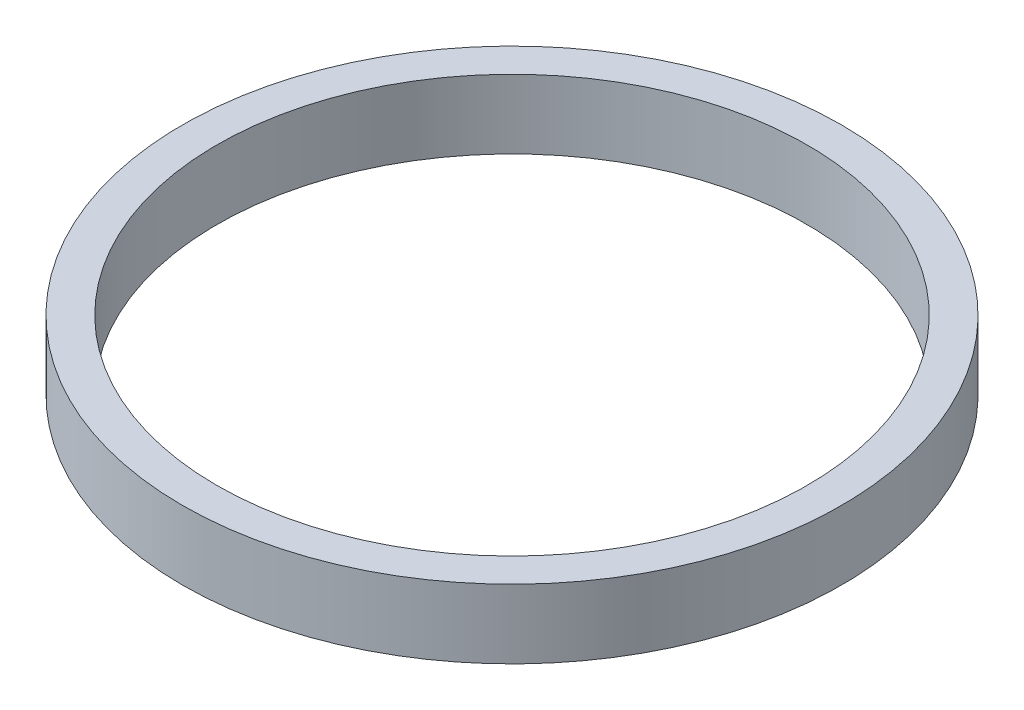
SolidWorks part; units mm, degrees
ref_plane "Front Plane" through (0, 0, 0) normal (0, 0, 1) x (1, 0, 0)
ref_plane "Top Plane" through (0, 0, 0) normal (0, 1, 0) x (1, 0, 0)
ref_plane "Right Plane" through (0, 0, 0) normal (1, 0, 0) x (0, 0, -1)
sketch "Sketch1" plane through (0, 0, 0) normal (0, 1, 0) x (1, 0, 0)
  circle A0 centre (0, 0) radius 42.75
  circle A1 centre (0, 0) radius 47.75
  dimension "D1" = 85.5
  dimension "D2" = 95.5
extrude "Boss-Extrude1" add sketch "Sketch1" along normal blind 10
